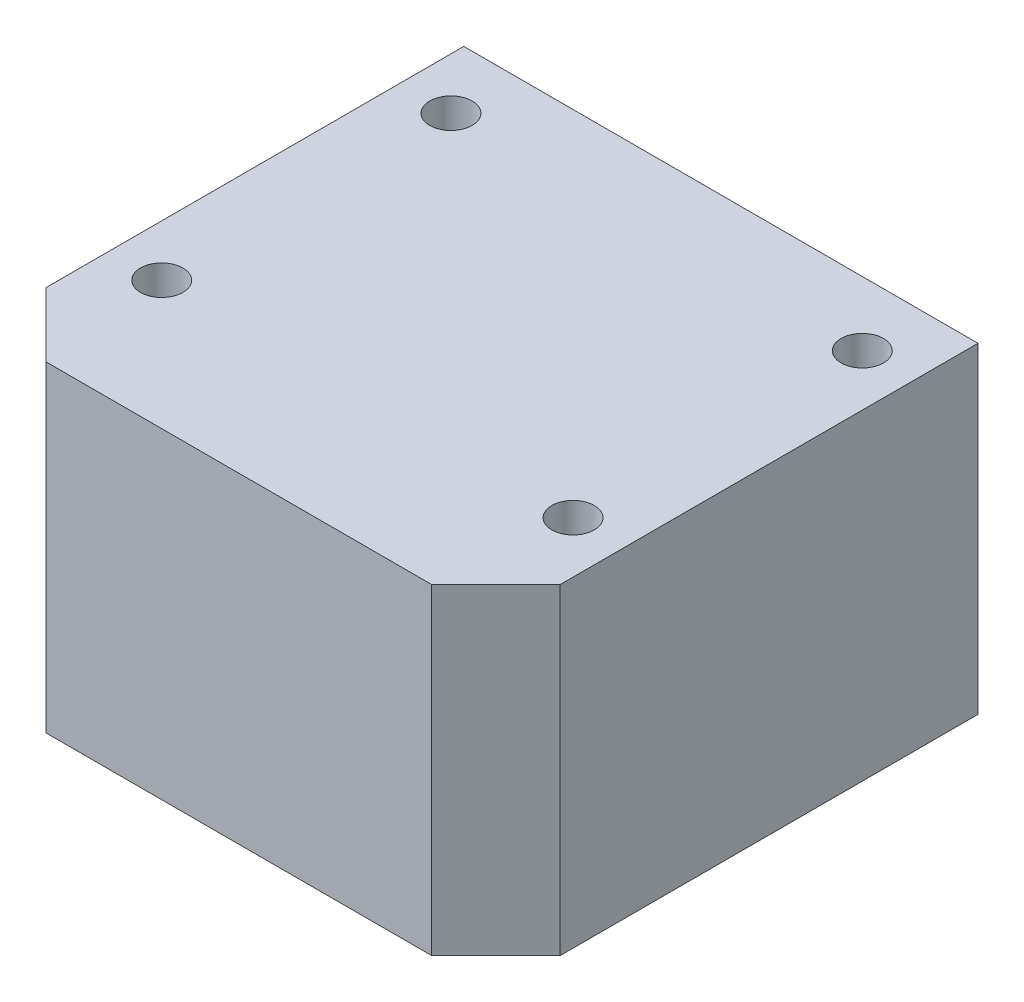
SolidWorks part; units mm, degrees
material "6061 Alloy"
ref_plane "Front Plane" through (0, 0, 0) normal (0, 0, 1) x (1, 0, 0)
ref_plane "Top Plane" through (0, 0, 0) normal (0, 1, 0) x (1, 0, 0)
ref_plane "Right Plane" through (0, 0, 0) normal (1, 0, 0) x (0, 0, -1)
sketch "Sketch1" plane through (0, 0, 0) normal (0, 1, 0) x (1, 0, 0)
  circle A0 centre (0, 0) radius 14
  point P3 (-16, 15)
  point P4 (-16, -7.5)
  dimension "D4" = 28
  dimension "D1" = 7.5
  dimension "D2" = 15
  dimension "D3" = 16
sketch "Sketch2" plane through (0, 0, 0) normal (0, 1, 0) x (1, 0, 0)
  line L0 (-16, 15) -> (-16, -7.5) construction
  line L1 (20, -12.5) -> (-20, -12.5)
  line L2 (20, -12.5) -> (20, 20)
  line L3 (20, 20) -> (-20, 20)
  line L4 (-20, -12.5) -> (-20, 20)
  line L5 (20, -12.5) -> (-20, 20) construction
  line L6 (20, 20) -> (-20, -12.5) construction
  line L7 (-16, 3.75) -> (0, 3.75) construction
  point P0 (0, 3.75)
  dimension "D1" = 32.5
  dimension "D2" = 40
extrude "Boss-Extrude1" add sketch "Sketch2" along normal blind 25
sketch "Sketch3" plane through (0, 0, 0) normal (0, -1, 0) x (1, 0, 0)
  line L0 (-20, 12.5) -> (20, 12.5) construction
  line L1 (-20, 12.5) -> (20, 12.5)
  line L2 (-20, 12.5) -> (-20, 17.5)
  line L3 (-20, 17.5) -> (20, 17.5)
  line L4 (20, 12.5) -> (20, 17.5)
  dimension "D1" = 5
extrude "Boss-Extrude2" add sketch "Sketch3" against normal up to surface (25 mm away) up to face at (0, 25, -3.75)
extrude "Cut-Extrude1" cut sketch "Sketch1" along normal blind 9 contours A0
chamfer "Chamfer1" distance 1 angle 45 1 edges at (0, 0, 14)
hole_wizard "M4 Tapped Hole2" positions "Sketch6" profile "Sketch7" tap size "M4" standard "GB"
sketch "Sketch6" plane through (0, 0, -20) normal (0, 0, -1) x (-1, 0, 0)
  line L0 (-20, 25) -> (20, 25) construction
  point P0 (0, 17)
  dimension "D1" = 8
sketch "Sketch7" plane through (0, 17, -20) normal (1, 0, 0) x (0, 1, 0)
  line L0 (0, 0) -> (0, 10.9914)
  line L1 (0, 10.9914) -> (1.65, 10)
  line L2 (1.65, 10) -> (1.65, 0)
  line L5 (1.65, 0) -> (0, 0)
  line L10 (0, 10.9914) -> (-1.65, 10) construction
  line L11 (0, -6.35) -> (0, 107.95) construction
  dimension "Tap Drill Dia." = 3.3
  dimension "Tap Drill Depth" = 10
  dimension "Drill Angle" = 118
cosmetic thread "Hole Thread5" parameters "D1"=10, "D2"=4
chamfer "Chamfer2" distance 5 angle 45 2 edges at (20, 12.5, 17.5) (-20, 12.5, 17.5)
hole_wizard "M4 Tapped Hole3" positions "Sketch8" profile "Sketch9" tap size "M4" standard "GB"
sketch "Sketch8" plane through (0, 25, 0) normal (0, 1, 0) x (1, 0, 0)
  line L0 (0, -13.75) -> (0, 13.75) construction
  point P0 (-16, 15)
  point P3 (-16, -7.5)
  point P9 (16, -7.5)
  point P10 (16, 15)
sketch "Sketch9" plane through (-16, 25, -15) normal (1, 0, 0) x (0, 0, 1)
  line L0 (0, 0) -> (0, 13.0914)
  line L1 (0, 13.0914) -> (1.65, 12.1)
  line L2 (1.65, 12.1) -> (1.65, 0)
  line L5 (1.65, 0) -> (0, 0)
  line L10 (0, 13.0914) -> (-1.65, 12.1) construction
  line L11 (0, -6.35) -> (0, 107.95) construction
  dimension "Tap Drill Dia." = 3.3
  dimension "Tap Drill Depth" = 12.1
  dimension "Drill Angle" = 118
cosmetic thread "Hole Thread6" parameters "D1"=10, "D2"=4
cosmetic thread "Hole Thread7" parameters "D1"=10, "D2"=4
cosmetic thread "Hole Thread8" parameters "D1"=10, "D2"=4
cosmetic thread "Hole Thread9" parameters "D1"=10, "D2"=4
